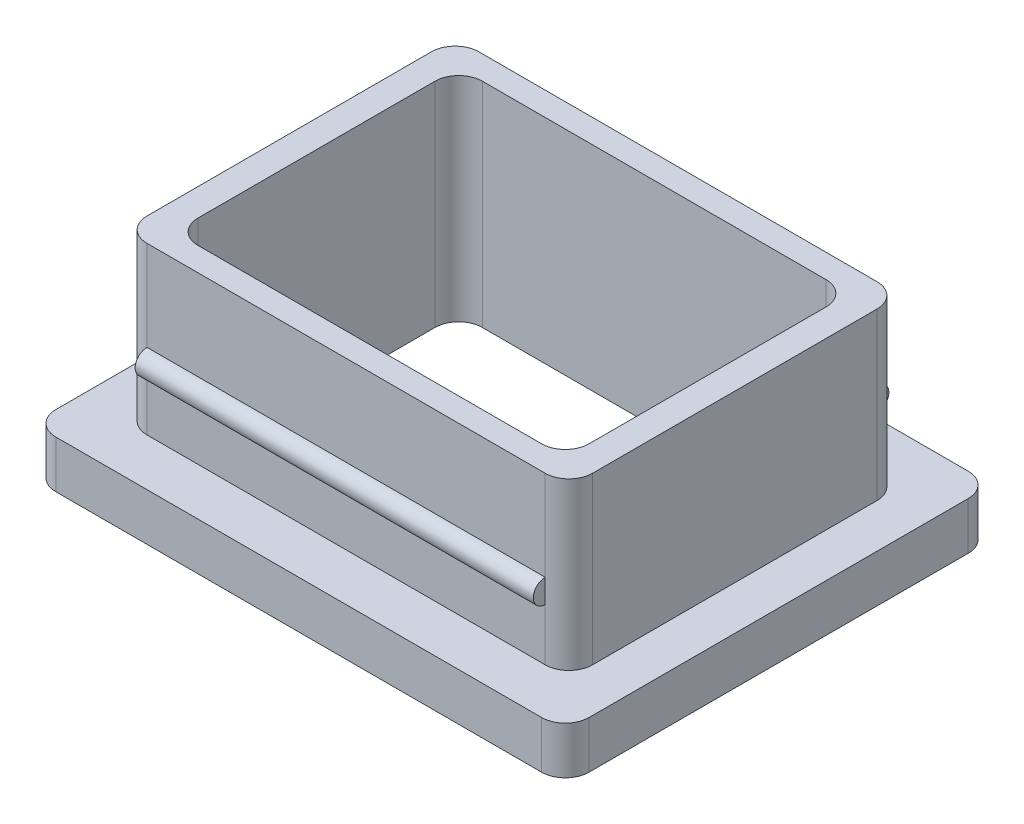
SolidWorks part; units mm, degrees
ref_plane "Front Plane" through (0, 0, 0) normal (0, 0, 1) x (1, 0, 0)
ref_plane "Top Plane" through (0, 0, 0) normal (0, 1, 0) x (1, 0, 0)
ref_plane "Right Plane" through (0, 0, 0) normal (1, 0, 0) x (0, 0, -1)
sketch "Sketch1" plane through (0, 0, 0) normal (0, 1, 0) x (1, 0, 0)
  line L1 (-8.25, -6) -> (8.25, -6)
  line L2 (-8.25, -6) -> (-8.25, 6)
  line L3 (-8.25, 6) -> (8.25, 6)
  line L4 (8.25, -6) -> (8.25, 6)
  line L5 (-8.25, -6) -> (8.25, 6) construction
  line L6 (-8.25, 6) -> (8.25, -6) construction
  line L7 (-9.4, -7) -> (9.4, -7)
  line L8 (-9.4, -7) -> (-9.4, 7)
  line L9 (-9.4, 7) -> (9.4, 7)
  line L10 (9.4, -7) -> (9.4, 7)
  line L11 (-9.4, -7) -> (9.4, 7) construction
  line L12 (-9.4, 7) -> (9.4, -7) construction
  point P0 (0, 0)
  point P6 (0, 0)
  dimension "D1" = 16.5
  dimension "D2" = 12
  dimension "D3" = 18.8
  dimension "D4" = 14
extrude "Boss-Extrude1" add sketch "Sketch1" along normal blind 7
sketch "Sketch2" plane through (0, 0, 0) normal (0, 1, 0) x (1, 0, 0)
  line L1 (-11.25, 9) -> (11.25, 9)
  line L2 (-11.25, 9) -> (-11.25, -9)
  line L3 (-11.25, -9) -> (11.25, -9)
  line L4 (11.25, 9) -> (11.25, -9)
  line L5 (-11.25, 9) -> (11.25, -9) construction
  line L6 (-11.25, -9) -> (11.25, 9) construction
  line L10 (-9.4, -7) -> (9.4, -7)
  line L11 (9.4, -7) -> (9.4, 7)
  line L12 (9.4, 7) -> (-9.4, 7)
  line L13 (-9.4, 7) -> (-9.4, -7)
  line L14 (-9.4, -7) -> (9.4, -7)
  line L15 (9.4, -7) -> (9.4, 7)
  line L16 (9.4, 7) -> (-9.4, 7)
  line L17 (-9.4, 7) -> (-9.4, -7)
  line L18 (-8.25, -6) -> (8.25, -6)
  line L19 (8.25, -6) -> (8.25, 6)
  line L20 (8.25, 6) -> (-8.25, 6)
  line L21 (-8.25, 6) -> (-8.25, -6)
  line L22 (-8.25, -6) -> (8.25, -6)
  line L23 (8.25, -6) -> (8.25, 6)
  line L24 (8.25, 6) -> (-8.25, 6)
  line L25 (-8.25, 6) -> (-8.25, -6)
  point P0 (0, 0)
  dimension "D3" = 18
  dimension "D4" = 22.5
  dimension "D1" = 0
  dimension "D2" = 0
extrude "Boss-Extrude2" add sketch "Sketch2" against normal blind 2 contours L16 L17 L14 L15 L25 L24 L23 L22 | L4 L1 L2 L3 L17 L16 L15 L14
sketch "Sketch4" plane through (0, 0, 0) normal (1, 0, 0) x (0, 0, -1)
  line L0 (-7, 7) -> (-7, 0) construction
  line L1 (-7, 7) -> (-7, 0)
  line L2 (7, 7) -> (7, 0) construction
  line L3 (7, 7) -> (7, 0)
  line L4 (0, 0) -> (0, 7) construction
  line L5 (-7, 7) -> (7, 7) construction
  circle A0 centre (-7, 6.5) radius 0.5
  circle A1 centre (7, 6.5) radius 0.5
  dimension "D1" = 1
extrude "Boss-Extrude4" [suppressed] add sketch "Sketch4" against normal up to surface and the other way up to surface contours L1 A0 | A1 L3
fillet "Fillet2" radius 1 12 edges at (8.25, 2.5, 6) (8.25, 2.5, -6) (-8.25, 2.5, 6) (-8.25, 2.5, -6) (11.25, -1, -9) (-11.25, -1, -9) (11.25, -1, 9) (-11.25, -1, 9) (9.4, 3.5, 7) (-9.4, 3.5, 7) (9.4, 3.5, -7) (-9.4, 3.5, -7)
sketch "Sketch6" plane through (-9.4, 0, 0) normal (-1, 0, 0) x (0, 0, 1)
  line L0 (-7, 7) -> (-7, 0) construction
  line L1 (-7, 7) -> (-7, 0)
  line L2 (0, 0) -> (0, 7) construction
  line L3 (-6, 7) -> (6, 7) construction
  line L4 (7, 7) -> (7, 0)
  circle A0 centre (-7, 2.7) radius 0.5
  circle A1 centre (7, 2.7) radius 0.5
  dimension "D1" = 1
  dimension "D2" = 2.7
extrude "Boss-Extrude5" [suppressed] add sketch "Sketch6" against normal up to surface (14.5 mm away) contours L1 A0 | A1 L4
ref_plane "Plane1" through (-8.4, 0, 0) normal (1, 0, 0) x (0, 0, -1)
sketch "Sketch7" plane through (-8.4, 0, 0) normal (1, 0, 0) x (0, 0, -1)
  line L0 (7, 0) -> (7, 7) construction
  line L1 (7, 0) -> (7, 7)
  line L2 (0, 0) -> (0, 7) construction
  line L3 (6, 7) -> (-6, 7) construction
  line L4 (-7, 0) -> (-7, 7)
  circle A0 centre (7, 2.7) radius 0.5
  circle A1 centre (-7, 2.7) radius 0.5
  dimension "D1" = 1
  dimension "D2" = 2.7
extrude "Boss-Extrude6" add sketch "Sketch7" along normal up to vertex (16.8 mm away) contours L1 A0 | A1 L4 up to point (8.4, 7, -7)
